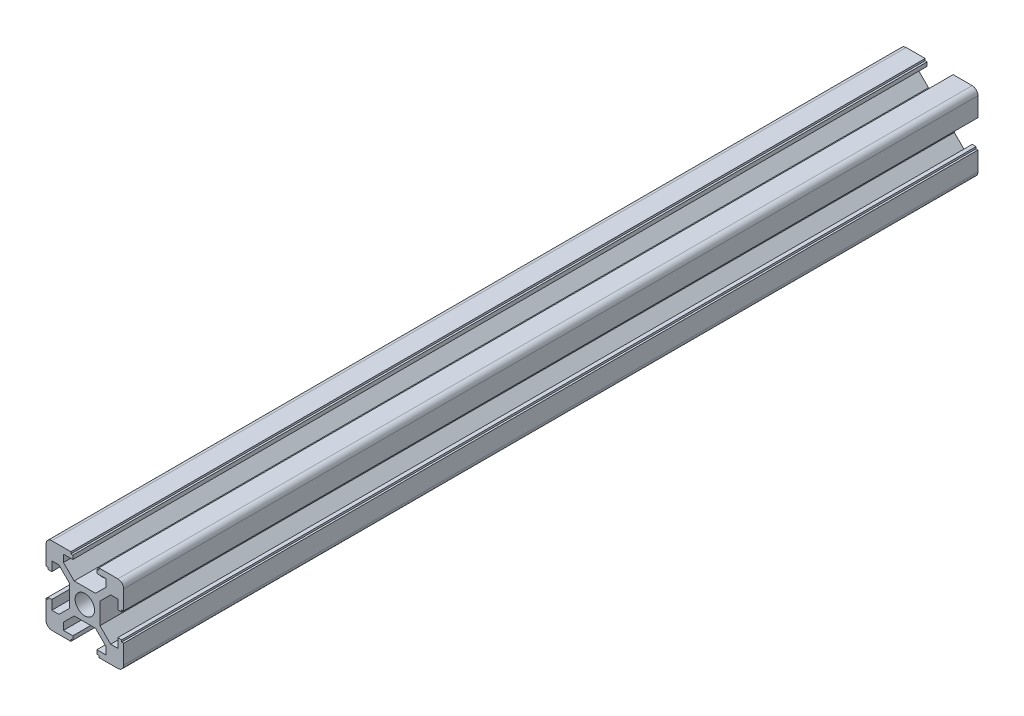
SolidWorks part; units mm, degrees
ref_plane "Plane1" through (0, 0, 0) normal (0, 0, 1) x (1, 0, 0)
ref_plane "Plane2" through (0, 0, 0) normal (0, 1, 0) x (1, 0, 0)
ref_plane "Plane3" through (0, 0, 0) normal (1, 0, 0) x (0, 0, -1)
sketch "Sketch1" plane through (0, 0, 0) normal (0, 0, 1) x (1, 0, 0)
  line L0 (-3.6, 10) -> (-3.6, 9.5)
  line L1 (-3.6, 9.5) -> (-3.1, 9.5)
  line L2 (-3.1, 9.5) -> (-3.1, 8.5)
  line L3 (-3.1, 8.5) -> (-5.5, 8.5)
  line L4 (-8.5, -10) -> (-3.6, -10)
  line L5 (-10, -8.5) -> (-10, -3.6)
  line L6 (8.5, 10) -> (3.6, 10)
  line L7 (10, 8.5) -> (10, 3.6)
  line L8 (0, 14.8756) -> (0, 0) construction
  line L9 (0, 0) -> (14.1675, 0) construction
  line L10 (-5.5, 8.5) -> (-5.5, 6.65)
  line L11 (-5.5, 6.65) -> (-2.75, 3.9)
  line L12 (-2.75, 3.9) -> (2.75, 3.9)
  line L13 (5.5, 6.65) -> (2.75, 3.9)
  line L14 (5.5, 8.5) -> (5.5, 6.65)
  line L15 (3.1, 8.5) -> (5.5, 8.5)
  line L16 (3.1, 9.5) -> (3.1, 8.5)
  line L17 (3.6, 9.5) -> (3.1, 9.5)
  line L18 (3.6, 10) -> (3.6, 9.5)
  line L19 (-3.6, 10) -> (-8.5, 10)
  line L20 (10, 3.6) -> (9.5, 3.6)
  line L21 (9.5, 3.6) -> (9.5, 3.1)
  line L22 (9.5, 3.1) -> (8.5, 3.1)
  line L23 (8.5, 3.1) -> (8.5, 5.5)
  line L24 (8.5, 5.5) -> (6.65, 5.5)
  line L25 (6.65, 5.5) -> (3.9, 2.75)
  line L26 (3.9, 2.75) -> (3.9, -2.75)
  line L27 (6.65, -5.5) -> (3.9, -2.75)
  line L28 (8.5, -5.5) -> (6.65, -5.5)
  line L29 (8.5, -3.1) -> (8.5, -5.5)
  line L30 (9.5, -3.1) -> (8.5, -3.1)
  line L31 (9.5, -3.6) -> (9.5, -3.1)
  line L32 (10, -3.6) -> (9.5, -3.6)
  line L33 (3.6, -10) -> (3.6, -9.5)
  line L34 (3.6, -9.5) -> (3.1, -9.5)
  line L35 (3.1, -9.5) -> (3.1, -8.5)
  line L36 (3.1, -8.5) -> (5.5, -8.5)
  line L37 (5.5, -8.5) -> (5.5, -6.65)
  line L38 (5.5, -6.65) -> (2.75, -3.9)
  line L39 (2.75, -3.9) -> (-2.75, -3.9)
  line L40 (-5.5, -6.65) -> (-2.75, -3.9)
  line L41 (-5.5, -8.5) -> (-5.5, -6.65)
  line L42 (-3.1, -8.5) -> (-5.5, -8.5)
  line L43 (-3.1, -9.5) -> (-3.1, -8.5)
  line L44 (-3.6, -9.5) -> (-3.1, -9.5)
  line L45 (-3.6, -10) -> (-3.6, -9.5)
  line L46 (-10, -3.6) -> (-9.5, -3.6)
  line L47 (-9.5, -3.6) -> (-9.5, -3.1)
  line L48 (-9.5, -3.1) -> (-8.5, -3.1)
  line L49 (-8.5, -3.1) -> (-8.5, -5.5)
  line L50 (-8.5, -5.5) -> (-6.65, -5.5)
  line L51 (-6.65, -5.5) -> (-3.9, -2.75)
  line L52 (-3.9, -2.75) -> (-3.9, 2.75)
  line L53 (-6.65, 5.5) -> (-3.9, 2.75)
  line L54 (-8.5, 5.5) -> (-6.65, 5.5)
  line L55 (-8.5, 3.1) -> (-8.5, 5.5)
  line L56 (-9.5, 3.1) -> (-8.5, 3.1)
  line L57 (-9.5, 3.6) -> (-9.5, 3.1)
  line L58 (-10, 3.6) -> (-9.5, 3.6)
  line L59 (3.6, -10) -> (8.5, -10)
  line L60 (-10, 3.6) -> (-10, 8.5)
  line L61 (10, -3.6) -> (10, -8.5)
  circle A0 centre (0, 0) radius 2.5
  arc A1 (-10, 8.5) -> (-8.5, 10) centre (-8.5, 8.5) cw
  arc A2 (10, 8.5) -> (8.5, 10) centre (8.5, 8.5) ccw
  arc A3 (-8.5, -10) -> (-10, -8.5) centre (-8.5, -8.5) cw
  arc A4 (8.5, -10) -> (10, -8.5) centre (8.5, -8.5) ccw
  point P0 (-10, 0)
  point P1 (10, 0)
  point P2 (0, 10)
  point P3 (0, -10)
  point P4 (0, 0)
  point P5 (-10, -10)
  point P6 (10, -10)
  point P7 (10, 10)
  point P8 (-10, 10)
  point P36 (-10, 10)
  point P39 (10, 10)
extrude "凸台-拉伸1" add sketch "Sketch1" along normal blind 220
sketch "草图1" plane through (0, 3.9, 0) normal (0, 1, 0) x (1, 0, 0)
  line L0 (2.75, -220) -> (-2.75, -220) construction
  circle A0 centre (0, -214) radius 1.5
  circle A1 centre (0, -6) radius 1.5
  point P0 (0, -214)
  dimension "D2" = 2
  dimension "D1" = 6
extrude "切除-拉伸1" cut sketch "草图1" against normal through all
